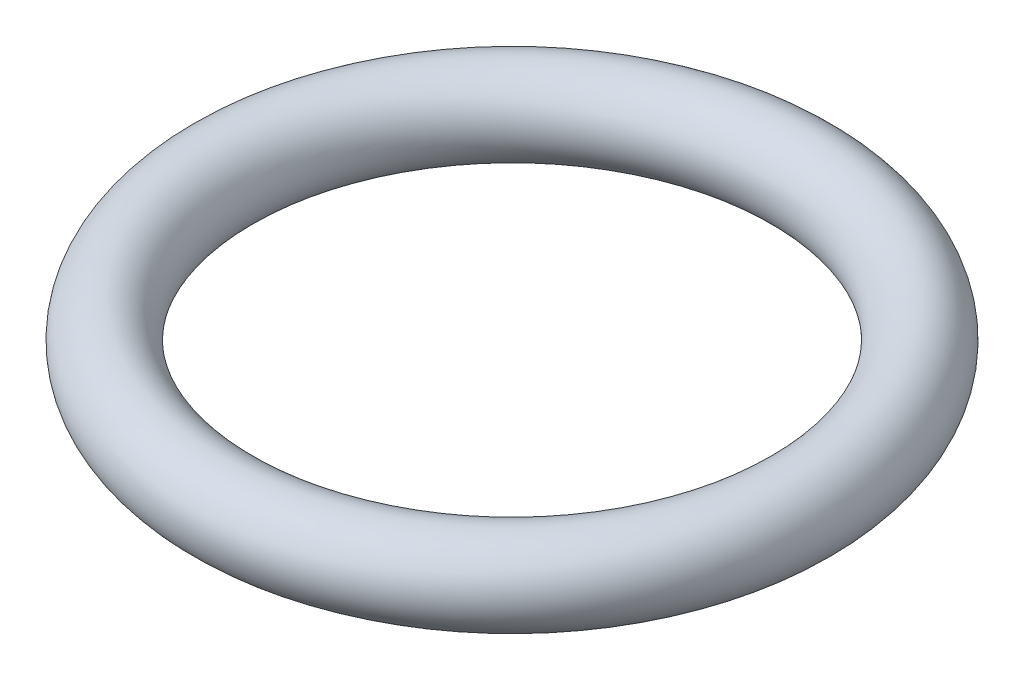
SolidWorks part; units mm, degrees
material "Резина"
ref_plane "Спереди" through (0, 0, 0) normal (0, 0, 1) x (1, 0, 0)
ref_plane "Сверху" through (0, 0, 0) normal (0, 1, 0) x (1, 0, 0)
ref_plane "Справа" through (0, 0, 0) normal (1, 0, 0) x (0, 0, -1)
sketch "Эскиз1" plane through (0, 0, 0) normal (0, 0, 1) x (1, 0, 0)
  line L0 (-147.7989, 0) -> (7242.1473, 0) construction
  line L1 (0, -1000) -> (0, 49000) construction
  circle A0 centre (-17.5, 0) radius 2.5
  dimension "D1" = 5
  dimension "D2" = 17.5
revolve "Повернуть1" add sketch "Эскиз1" angle 360 about L1
